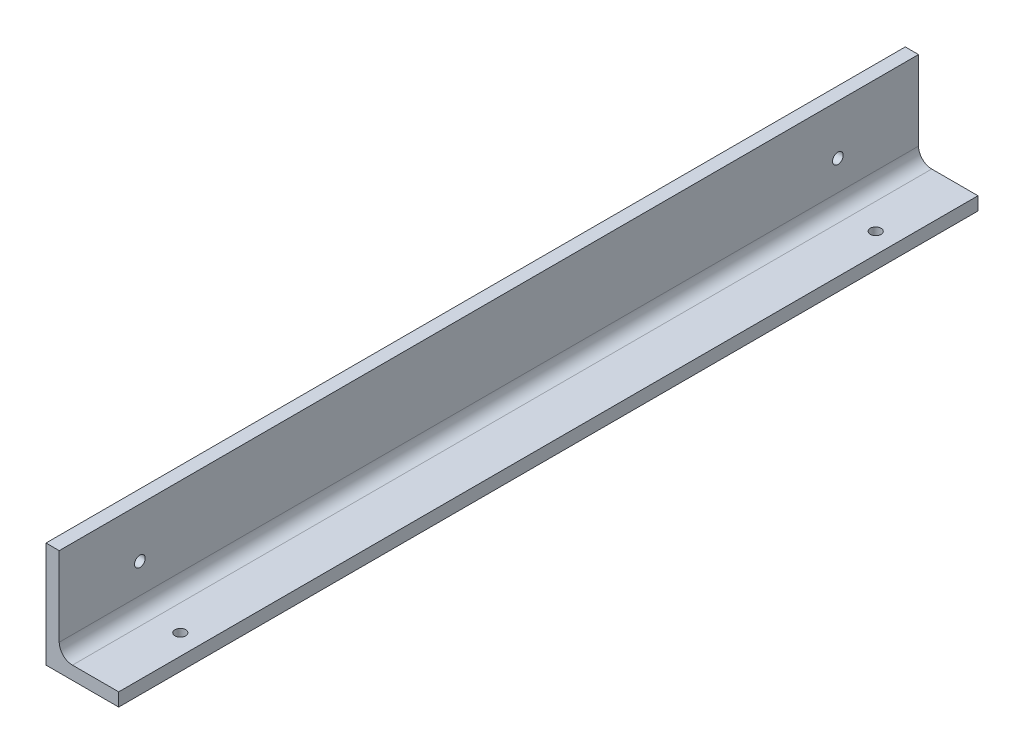
SolidWorks part; units mm, degrees
material "1060 Alloy"
ref_plane "Front Plane" through (0, 0, 0) normal (0, 0, 1) x (1, 0, 0)
ref_plane "Top Plane" through (0, 0, 0) normal (0, 1, 0) x (1, 0, 0)
ref_plane "Right Plane" through (0, 0, 0) normal (1, 0, 0) x (0, 0, -1)
sketch "Sketch1" plane through (0, 0, 0) normal (0, 0, 1) x (1, 0, 0)
  line L0 (0, 0) -> (0, 50.8)
  line L1 (0, 50.8) -> (6.35, 50.8)
  line L2 (6.35, 50.8) -> (6.35, 12.7)
  line L3 (12.7, 6.35) -> (34.925, 6.35)
  line L4 (34.925, 6.35) -> (34.925, 0)
  line L5 (34.925, 0) -> (0, 0)
  arc A0 (6.35, 12.7) -> (12.7, 6.35) centre (12.7, 12.7) ccw
  dimension "D4" = 6.35
  dimension "D1" = 6.35
  dimension "D2" = 50.8
  dimension "D3" = 34.925
extrude "Boss-Extrude1" add sketch "Sketch1" along normal up to surface (412.75 mm away)
sketch "Sketch2" plane through (6.35, 0, 0) normal (1, 0, 0) x (0, 0, -1)
  circle A0 centre (-374.015, 27.0002) radius 2.5797
  circle A1 centre (-38.735, 26.9875) radius 2.5797
  dimension "D1" = 5.1594
  dimension "D2" = 5.1594
extrude "Cut-Extrude1" cut sketch "Sketch2" against normal through all
sketch "Sketch3" plane through (0, 6.35, 0) normal (0, 1, 0) x (1, 0, 0)
  line L0 (34.925, -412.75) -> (34.925, 0) construction
  line L1 (12.7, -412.75) -> (34.925, -412.75) construction
  line L2 (34.925, 0) -> (12.7, 0) construction
  circle A0 centre (25.146, -373.38) radius 2.5797
  circle A1 centre (25.146, -39.37) radius 2.5797
  dimension "D5" = 5.1594
  dimension "D6" = 5.1594
  dimension "D1" = 9.779
  dimension "D2" = 39.37
  dimension "D3" = 39.37
  dimension "D4" = 9.779
extrude "Cut-Extrude2" cut sketch "Sketch3" against normal through all
